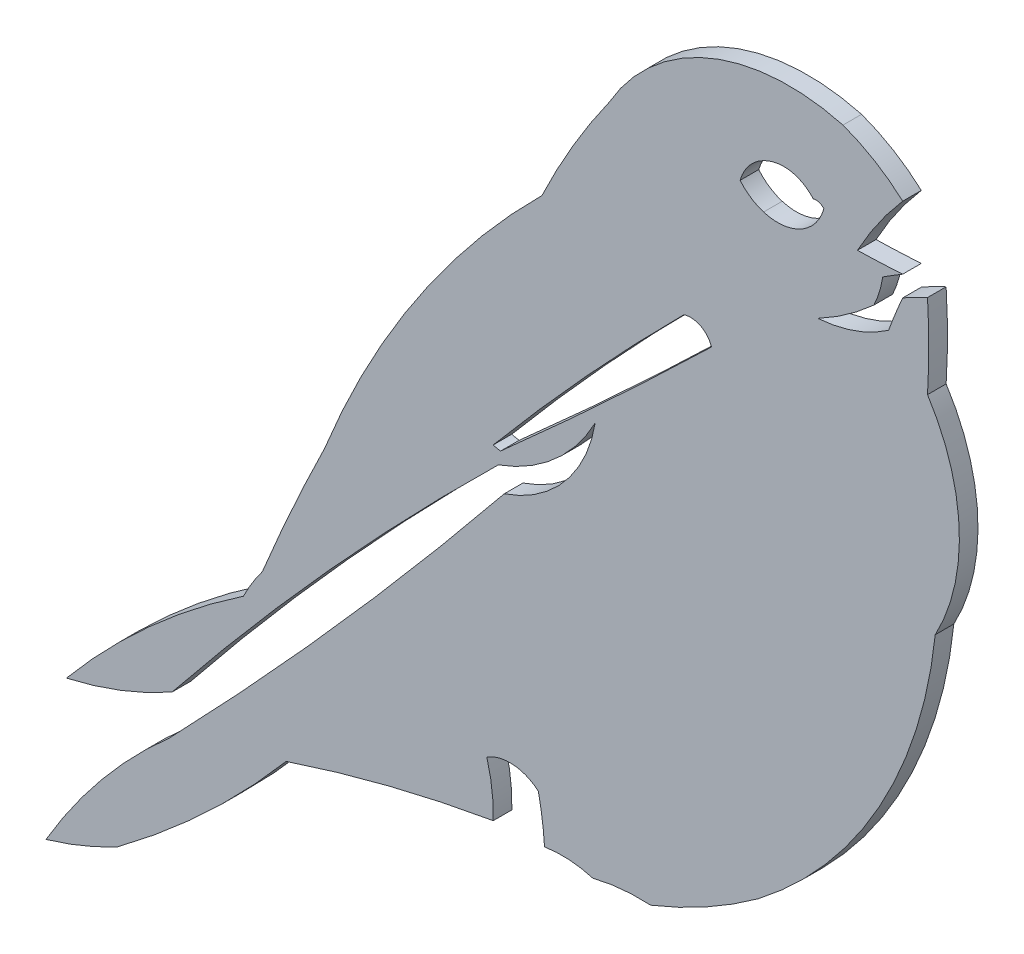
SolidWorks part; units mm, degrees
ref_plane "정면" through (0, 0, 0) normal (0, 0, 1) x (1, 0, 0)
ref_plane "윗면" through (0, 0, 0) normal (0, 1, 0) x (1, 0, 0)
ref_plane "우측면" through (0, 0, 0) normal (1, 0, 0) x (0, 0, -1)
sketch "스케치1" plane through (0, 0, 0) normal (0, 0, 1) x (1, 0, 0)
  arc A0 (4.2439, 6.1181) -> (3.6018, 5.7204) centre (20.5887, -20.9847) ccw
  arc A1 (-9.1556, -14.0567) -> (-7.4947, -14.1789) centre (-8.4075, -15.2371) cw
  arc A2 (-2.8082, 1.4606) -> (-8.9494, -5.2434) centre (71.8389, -73.0843) ccw
  arc A3 (-8.9494, -5.2434) -> (-8.7114, -5.2951) centre (-8.5906, -4.1637) ccw
  arc A4 (-8.7114, -5.2951) -> (-1.916, 1.0046) centre (-147.597, 151.334) ccw
  arc A5 (-2.8082, 1.4606) -> (-1.916, 1.0046) centre (-2.5901, 0.7865) cw
  arc A6 (-7.4947, -14.1789) -> (-7.2968, -15.6335) centre (-17.187, -16.2381) cw
  arc A7 (-0.9939, 6.1181) -> (0.2151, 7.1923) centre (0.4412, 5.7204) cw
  arc A8 (0.2151, 7.1923) -> (1.3613, 6.7793) centre (0.4134, 5.9456) cw
  arc A9 (1.3613, 6.7793) -> (1.7028, 6.6709) centre (1.4511, 6.4702) cw
  arc A10 (1.7028, 6.6709) -> (-0.238, 5.6113) centre (0.2157, 7.0874) cw
  arc A11 (-0.238, 5.6113) -> (-0.9939, 6.1181) centre (0.2257, 7.1199) cw
  arc A12 (-7.2968, -15.6335) -> (-5.7407, -15.7284) centre (-6.7285, -19.12) cw
  arc A65 (4.2439, 8.1547) -> (2.7862, 6.0557) centre (12.9608, 0.5455) ccw
  arc A66 (2.7862, 6.0557) -> (4.2439, 6.1181) centre (2.1695, 37.517) ccw
  arc A67 (2.3188, 9.3164) -> (4.2439, 8.1547) centre (0.3375, 3.8572) cw
  arc A68 (2.3188, 9.3164) -> (-5.2102, 6.1917) centre (0.5799, 2.8734) ccw
  arc A69 (-5.2102, 6.1917) -> (-7.3807, 2.4989) centre (14.5676, -7.9177) ccw
  arc A70 (-7.3807, 2.4989) -> (-14.3748, -8.04) centre (14.4232, -19.5614) ccw
  arc A71 (-14.3748, -8.04) -> (-16.3869, -12.496) centre (50.0982, -39.8352) ccw
  arc A72 (-16.3869, -12.496) -> (-16.9998, -13.491) centre (-11.3351, -16.2936) ccw
  arc A73 (-16.9998, -13.491) -> (-22.7017, -18.6259) centre (-1.7841, -36.1201) ccw
  arc A74 (-22.7017, -18.6259) -> (-19.298, -17.3142) centre (-25.4707, -6.3688) ccw
  arc A75 (-8.7873, -5.7207) -> (-19.298, -17.3142) centre (82.0831, -98.6654) ccw
  arc A76 (-5.6641, -2.9885) -> (-8.7873, -5.7207) centre (-10.7322, -0.3463) cw
  arc A77 (-5.6641, -2.9885) -> (-8.5937, -6.4288) centre (-9.9808, -2.28) cw
  arc A78 (-8.5937, -6.4288) -> (-19.3694, -18.6259) centre (-154.7242, 111.8122) cw
  arc A79 (-19.3694, -18.6259) -> (-23.3592, -23.4565) centre (-6.4213, -33.3833) ccw
  arc A80 (-23.3592, -23.4565) -> (-21.0531, -22.5111) centre (-26.7045, -12.0117) ccw
  arc A81 (-21.0531, -22.5111) -> (-15.621, -17.4102) centre (-40.7497, 3.9074) ccw
  arc A82 (-15.621, -17.4102) -> (-8.9494, -15.7284) centre (-1.1734, -60.6492) cw
  arc A93 (3.6018, 5.7204) -> (3.3163, 4.7915) centre (0.3331, 6.2167) cw
  arc A94 (3.3163, 4.7915) -> (1.5093, 3.5171) centre (-2.6617, 11.3496) cw
  arc A95 (1.5093, 3.5171) -> (3.7905, 4.3247) centre (1.1719, 8.0959) ccw
  arc A101 (-8.9494, -15.7284) -> (-9.1556, -14.0567) centre (-14.3835, -15.55) ccw
  arc A120 (-5.7407, -15.7284) -> (-3.8757, -15.55) centre (-4.2242, -21.7447) cw
  arc A130 (3.7905, 4.3247) -> (4.2439, 5.4552) centre (20.1711, -1.5876) cw
  arc A131 (4.2439, 5.4552) -> (5.0436, 5.8657) centre (9.4159, -3.6379) cw
  arc A132 (5.0436, 5.8657) -> (5.0436, 3.156) centre (-16.2873, 4.5109) cw
  arc A133 (5.0436, 3.156) -> (5.2918, -3.4195) centre (-0.3999, -0.3419) cw
  arc A134 (5.2918, -3.4195) -> (-0.4181, -13.6438) centre (-9.4338, -1.9024) cw
  arc A135 (-0.4181, -13.6438) -> (-3.8757, -15.55) centre (-9.7643, -0.7799) cw
  point P4 (8.1002, 10.5033)
  point P10 (7.6194, 8.7871)
  point P25 (8.5691, 9.4267)
  point P102 (19.7648, -8.2217)
  point P103 (3.7369, 5.7093)
  point P104 (-35.7803, 44.1958)
  point P105 (-0.7881, 1.5534)
  point P129 (7.0349, 9.1134)
  point P165 (-0.8207, -5.3596)
  point P245 (2.5924, -5.1763)
  point P246 (11.6519, 6.6775)
  point P247 (8.2363, 10.3567)
  point P248 (7.2118, 9.0201)
  point P249 (6.2716, 30.1002)
  point P250 (7.0396, 9.3361)
  point P251 (8.2228, 9.4137)
  point P252 (10.6854, -6.0401)
  point P253 (8.1311, 10.3056)
  point P254 (9.9738, 10.4887)
  point P258 (8.462, 9.5956)
extrude "보스-돌출1" add sketch "스케치1" along normal blind 0.6
